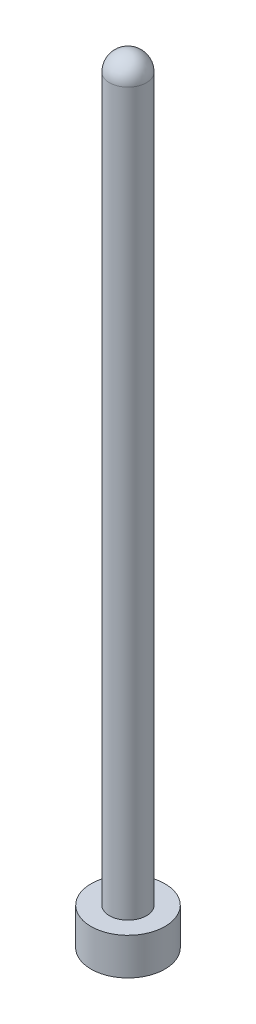
SolidWorks part; units mm, degrees
material "1100-H12 Rod (SS)"
ref_plane "Front Plane" through (0, 0, 0) normal (0, 0, 1) x (1, 0, 0)
ref_plane "Top Plane" through (0, 0, 0) normal (0, 1, 0) x (1, 0, 0)
ref_plane "Right Plane" through (0, 0, 0) normal (1, 0, 0) x (0, 0, -1)
sketch "Sketch1" plane through (0, 0, 0) normal (0, 1, 0) x (1, 0, 0)
  circle A0 centre (0, 0) radius 2.54
  dimension "D1" = 5.08
extrude "Boss-Extrude1" add sketch "Sketch1" along normal blind 2.54
sketch "Sketch2" plane through (0, 2.54, 0) normal (0, 1, 0) x (1, 0, 0)
  circle A0 centre (0, 0) radius 1.27
  dimension "D1" = 2.54
extrude "Boss-Extrude2" add sketch "Sketch2" along normal blind 50.8
fillet "Fillet7" radius 1.27 1 edges at (0, 53.34, 1.27)
sketch "Sketch3" plane through (0, 0, 0) normal (0, -1, 0) x (1, 0, 0)
  circle A0 centre (0, 0) radius 1.27
  dimension "D1" = 2.54
extrude "Cut-Extrude1" cut sketch "Sketch3" against normal blind 1.27
